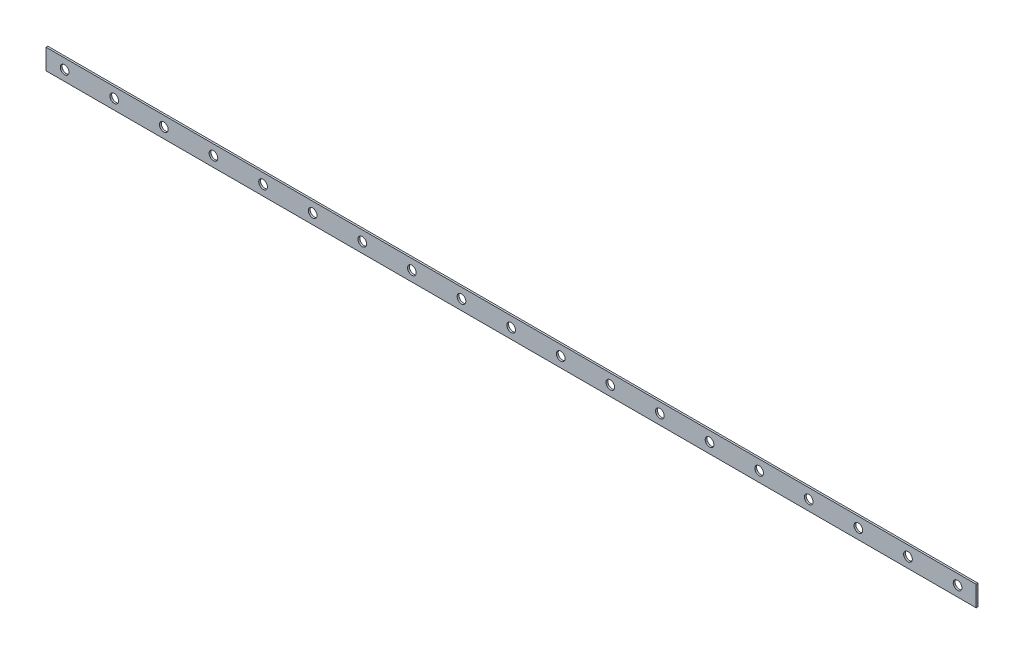
SolidWorks part; units mm, degrees
ref_plane "Alzado" through (0, 0, 0) normal (0, 0, 1) x (1, 0, 0)
ref_plane "Planta" through (0, 0, 0) normal (0, 1, 0) x (1, 0, 0)
ref_plane "Vista lateral" through (0, 0, 0) normal (1, 0, 0) x (0, 0, -1)
sketch "Sketch1" plane through (0, 0, 0) normal (0, 0, 1) x (1, 0, 0)
  line L1 (0, 0) -> (1500, 0)
  line L2 (0, 0) -> (0, 33)
  line L3 (0, 33) -> (1500, 33)
  line L4 (1500, 0) -> (1500, 33)
  dimension "D1" = 33
  dimension "D2" = 1500
extrude "Boss-Extrude1" add sketch "Sketch1" along normal blind 2.95
sketch "Sketch3" plane through (0, 0, 0) normal (0, 0, 1) x (1, 0, 0)
  line L0 (0, 33) -> (0, 0) construction
  line L1 (0, 33) -> (0, 0)
  line L2 (1500, 33) -> (0, 33) construction
  line L3 (0, 0) -> (1500, 0) construction
  line L4 (1500, 33) -> (0, 33)
  line L5 (0, 0) -> (1500, 0)
  line L8 (0, 26.715) -> (0, 6.285)
  line L9 (0, 6.285) -> (1500, 6.285)
  line L10 (1500, 6.285) -> (1500, 26.715)
  line L11 (1500, 26.715) -> (0, 26.715)
  arc A38 (1470, 9.5) -> (1470, 23.5) centre (1470, 16.5) ccw
  arc A39 (1470, 23.5) -> (1470, 9.5) centre (1470, 16.5) ccw
  arc A40 (1390, 9.5) -> (1390, 23.5) centre (1390, 16.5) ccw
  arc A41 (1390, 23.5) -> (1390, 9.5) centre (1390, 16.5) ccw
  arc A42 (1310, 9.5) -> (1310, 23.5) centre (1310, 16.5) ccw
  arc A43 (1310, 23.5) -> (1310, 9.5) centre (1310, 16.5) ccw
  arc A44 (1230, 9.5) -> (1230, 23.5) centre (1230, 16.5) ccw
  arc A45 (1230, 23.5) -> (1230, 9.5) centre (1230, 16.5) ccw
  arc A46 (1150, 9.5) -> (1150, 23.5) centre (1150, 16.5) ccw
  arc A47 (1150, 23.5) -> (1150, 9.5) centre (1150, 16.5) ccw
  arc A48 (1070, 9.5) -> (1070, 23.5) centre (1070, 16.5) ccw
  arc A49 (1070, 23.5) -> (1070, 9.5) centre (1070, 16.5) ccw
  arc A50 (990, 9.5) -> (990, 23.5) centre (990, 16.5) ccw
  arc A51 (990, 23.5) -> (990, 9.5) centre (990, 16.5) ccw
  arc A52 (910, 9.5) -> (910, 23.5) centre (910, 16.5) ccw
  arc A53 (910, 23.5) -> (910, 9.5) centre (910, 16.5) ccw
  arc A54 (830, 9.5) -> (830, 23.5) centre (830, 16.5) ccw
  arc A55 (830, 23.5) -> (830, 9.5) centre (830, 16.5) ccw
  arc A56 (750, 9.5) -> (750, 23.5) centre (750, 16.5) ccw
  arc A57 (750, 23.5) -> (750, 9.5) centre (750, 16.5) ccw
  arc A58 (670, 23.5) -> (670, 9.5) centre (670, 16.5) ccw
  arc A59 (670, 9.5) -> (670, 23.5) centre (670, 16.5) ccw
  arc A60 (590, 9.5) -> (590, 23.5) centre (590, 16.5) ccw
  arc A61 (590, 23.5) -> (590, 9.5) centre (590, 16.5) ccw
  arc A62 (510, 9.5) -> (510, 23.5) centre (510, 16.5) ccw
  arc A63 (510, 23.5) -> (510, 9.5) centre (510, 16.5) ccw
  arc A64 (430, 9.5) -> (430, 23.5) centre (430, 16.5) ccw
  arc A65 (430, 23.5) -> (430, 9.5) centre (430, 16.5) ccw
  arc A66 (350, 23.5) -> (350, 9.5) centre (350, 16.5) ccw
  arc A67 (350, 9.5) -> (350, 23.5) centre (350, 16.5) ccw
  arc A68 (270, 23.5) -> (270, 9.5) centre (270, 16.5) ccw
  arc A69 (270, 9.5) -> (270, 23.5) centre (270, 16.5) ccw
  arc A70 (190, 23.5) -> (190, 9.5) centre (190, 16.5) ccw
  arc A71 (190, 9.5) -> (190, 23.5) centre (190, 16.5) ccw
  arc A72 (110, 9.5) -> (110, 23.5) centre (110, 16.5) ccw
  arc A73 (110, 23.5) -> (110, 9.5) centre (110, 16.5) ccw
  arc A74 (30, 23.5) -> (30, 9.5) centre (30, 16.5) ccw
  arc A75 (30, 9.5) -> (30, 23.5) centre (30, 16.5) ccw
  dimension "D1" = 6.285
  dimension "D2" = 6.285
  dimension "D3" = 20.43
extrude "Cut-Extrude1" cut sketch "Sketch3" against normal through all and the other way through all contours A68 A69 | A66 A67 | A64 A65 | A62 A63 | A60 A61 | A58 A59 | A56 A57 | A54 A55 | A52 A53 | A50 A51 | A48 A49 | A46 A47 | A44 A45 | A42 A43 | A40 A41 | A38 A39 | A75 A74 | A72 A73 | A71 A70
